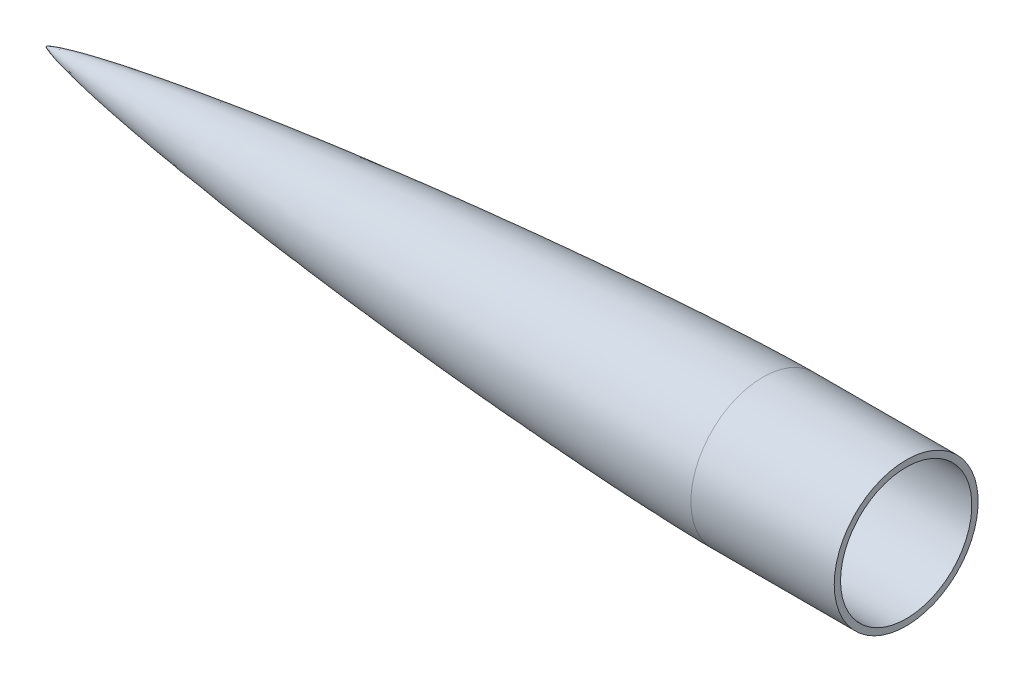
SolidWorks part; units mm, degrees
material "ABS"
ref_plane "Front Plane" through (0, 0, 0) normal (0, 0, 1) x (1, 0, 0)
ref_plane "Top Plane" through (0, 0, 0) normal (0, 1, 0) x (1, 0, 0)
ref_plane "Right Plane" through (0, 0, 0) normal (1, 0, 0) x (0, 0, -1)
sketch "Sketch1" plane through (0, 0, 0) normal (0, 0, 1) x (1, 0, 0)
  line L0 (0, 0) -> (158.75, 0) construction
  line L1 (158.7503, 15.9351) -> (190.5003, 15.9351)
  line L2 (0, 0) -> (158.75, 0)
  line L3 (158.75, 0) -> (158.75, 14.5415)
  line L4 (158.75, 14.5415) -> (190.5003, 14.5415)
  line L5 (190.5003, 14.5415) -> (190.5003, 15.9351)
  spline S0 degree 4 poles (0, 0) (0.0031, 0.0058) (0.0105, 0.0166) (0.0302, 0.0345) (0.0699, 0.0645) (0.1271, 0.1) (0.2089, 0.1446) (0.3241, 0.2006) (0.495, 0.2758) (0.7817, 0.389) (1.2933, 0.5682) (2.2344, 0.8569) (4.002, 1.3262) (7.0881, 2.0289) (12.3437, 3.0582) (19.5644, 4.273) (28.3208, 5.5714) (38.0626, 6.8651) (47.8184, 8.0472) (57.585, 9.1364) (67.3603, 10.1448) (77.1428, 11.0795) (86.9318, 11.945) (99.1751, 12.9429) (111.4271, 13.8291) (123.687, 14.5994) (135.9544, 15.2356) (144.3258, 15.5885) (151.2527, 15.8116) (155.7253, 15.9049) (157.7419, 15.9316) (158.7503, 15.9351) knots 0 0 0 0 0 0.000165 0.000329 0.000659 0.001247 0.001847 0.002662 0.003861 0.00592 0.009557 0.016226 0.028492 0.051678 0.088753 0.150237 0.211721 0.273205 0.334689 0.396173 0.457656 0.51914 0.580624 0.642108 0.765076 0.826559 0.888043 0.949527 0.974764 1 1 1 1 1 construction
  spline S1 degree 4 poles (0, 0) (0.0031, 0.0058) (0.0105, 0.0166) (0.0302, 0.0345) (0.0699, 0.0645) (0.1271, 0.1) (0.2089, 0.1446) (0.3241, 0.2006) (0.495, 0.2758) (0.7817, 0.389) (1.2933, 0.5682) (2.2344, 0.8569) (4.002, 1.3262) (7.0881, 2.0289) (12.3437, 3.0582) (19.5644, 4.273) (28.3208, 5.5714) (38.0626, 6.8651) (47.8184, 8.0472) (57.585, 9.1364) (67.3603, 10.1448) (77.1428, 11.0795) (86.9318, 11.945) (99.1751, 12.9429) (111.4271, 13.8291) (123.687, 14.5994) (135.9544, 15.2356) (144.3258, 15.5885) (151.2527, 15.8116) (155.7253, 15.9049) (157.7419, 15.9316) (158.7503, 15.9351) knots 0 0 0 0 0 0.000165 0.000329 0.000659 0.001247 0.001847 0.002662 0.003861 0.00592 0.009557 0.016226 0.028492 0.051678 0.088753 0.150237 0.211721 0.273205 0.334689 0.396173 0.457656 0.51914 0.580624 0.642108 0.765076 0.826559 0.888043 0.949527 0.974764 1 1 1 1 1
  dimension "D1" = 158.75
  dimension "D2" = 31.75
  dimension "D3" = 15.9351
  dimension "D4" = 14.5415
revolve "Revolve1" add sketch "Sketch1" angle 360 about L0
